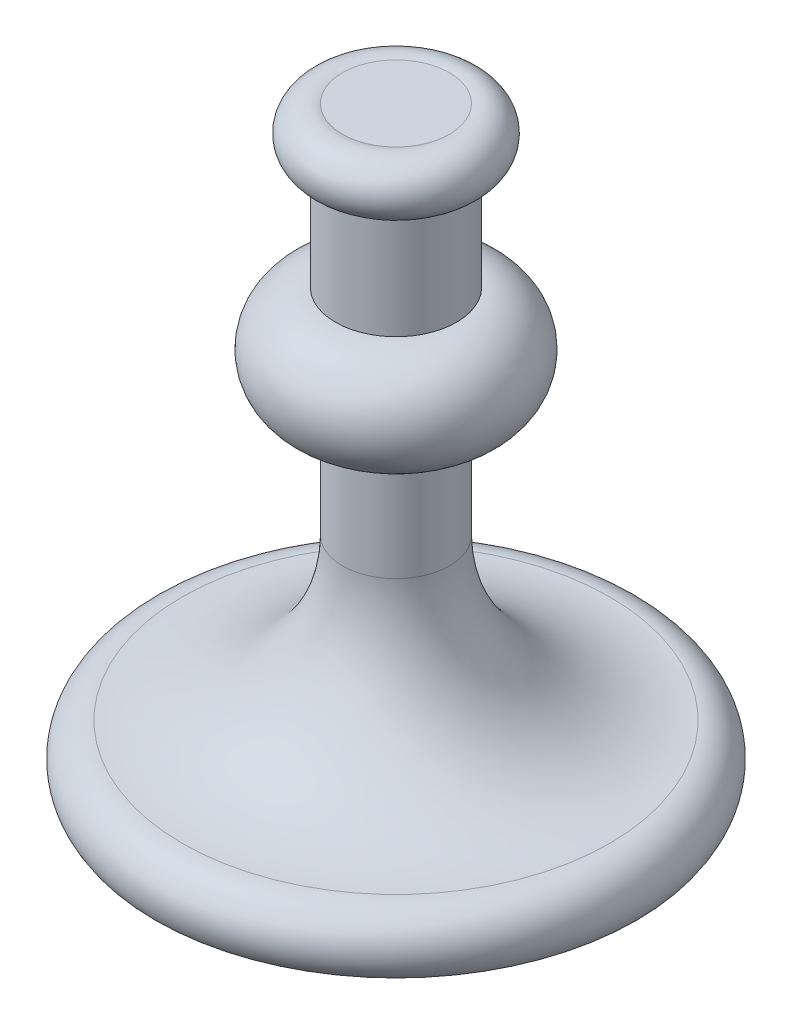
SolidWorks part; units mm, degrees
material "Maple"
ref_plane "Front Plane" through (0, 0, 0) normal (0, 0, 1) x (1, 0, 0)
ref_plane "Top Plane" through (0, 0, 0) normal (0, 1, 0) x (1, 0, 0)
ref_plane "Right Plane" through (0, 0, 0) normal (1, 0, 0) x (0, 0, -1)
sketch "Sketch1" plane through (0, 0, 0) normal (1, 0, 0) x (0, 0, -1)
  line L0 (-55.062, 79.5958) -> (-55.062, 39.5958)
  line L1 (-52.3852, 99.2309) -> (-32.3852, 99.2309)
  line L2 (-32.3852, 99.2309) -> (-32.3852, -120.7691)
  line L3 (-32.3852, -120.7691) -> (-122.3852, -120.7691)
  line L4 (-52.3852, -40.7691) -> (-52.3852, -0.2243)
  arc A0 (-55.062, 39.5958) -> (-52.3852, -0.2243) centre (-55.062, 19.5958) ccw
  arc A2 (-112.3852, -100.7691) -> (-122.3852, -120.7691) centre (-112.3852, -113.2691) ccw
  arc A3 (-55.062, 79.5958) -> (-52.3852, 99.2309) centre (-55.062, 89.5958) cw
  arc A4 (-112.3852, -100.7691) -> (-52.3852, -40.7691) centre (-112.3852, -40.7691) ccw
  dimension "D3" = 10
  dimension "D5" = 20
  dimension "D6" = 60
  dimension "D7" = 12.5
  dimension "D1" = 220
  dimension "D2" = 20
  dimension "D4" = 40
  dimension "D8" = 20
  dimension "D9" = 80
  dimension "D10" = 90
revolve "Revolve1" add sketch "Sketch1" angle 360 about L2
